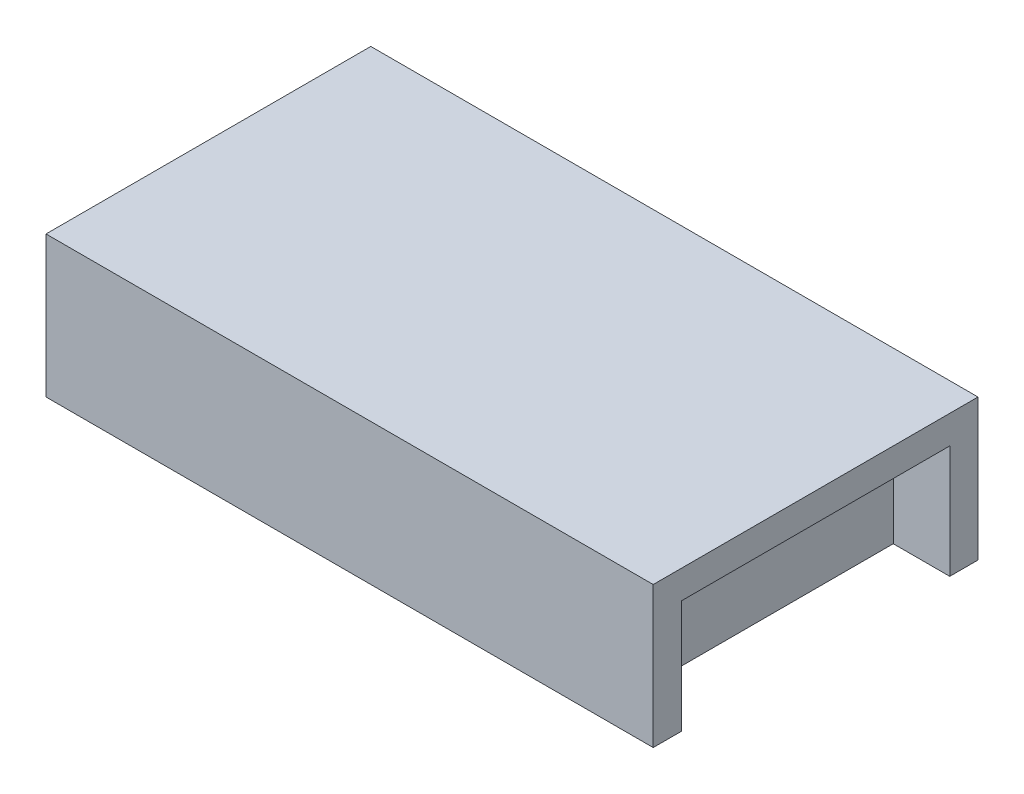
SolidWorks part; units mm, degrees
ref_plane "前视基准面" through (0, 0, 0) normal (0, 0, 1) x (1, 0, 0)
ref_plane "上视基准面" through (0, 0, 0) normal (0, 1, 0) x (1, 0, 0)
ref_plane "右视基准面" through (0, 0, 0) normal (1, 0, 0) x (0, 0, -1)
sketch "草图1" plane through (0, 0, 0) normal (0, 1, 0) x (1, 0, 0)
  line L1 (-107.5, -57.5) -> (107.5, -57.5)
  line L2 (-107.5, -57.5) -> (-107.5, 57.5)
  line L3 (-107.5, 57.5) -> (107.5, 57.5)
  line L4 (107.5, -57.5) -> (107.5, 57.5)
  line L5 (-107.5, -57.5) -> (107.5, 57.5) construction
  line L6 (-107.5, 57.5) -> (107.5, -57.5) construction
  point P0 (0, 0)
  dimension "D1" = 215
  dimension "D2" = 115
extrude "凸台-拉伸1" add sketch "草图1" along normal blind 50
sketch "草图2" plane through (0, 0, 0) normal (0, -1, 0) x (1, 0, 0)
  line L0 (107.5, 57.5) -> (107.5, -57.5) construction
  line L1 (107.5, 47.5) -> (87.5, 47.5)
  line L2 (107.5, 47.5) -> (107.5, -47.5)
  line L3 (107.5, -47.5) -> (87.5, -47.5)
  line L4 (87.5, 47.5) -> (87.5, -47.5)
  line L5 (-107.5, 57.5) -> (107.5, 57.5) construction
  line L6 (107.5, -57.5) -> (-107.5, -57.5) construction
  point P8 (97.5, -47.5)
  dimension "D1" = 20
  dimension "D2" = 10
  dimension "D3" = 10
extrude "切除-拉伸1" cut sketch "草图2" against normal blind 40
